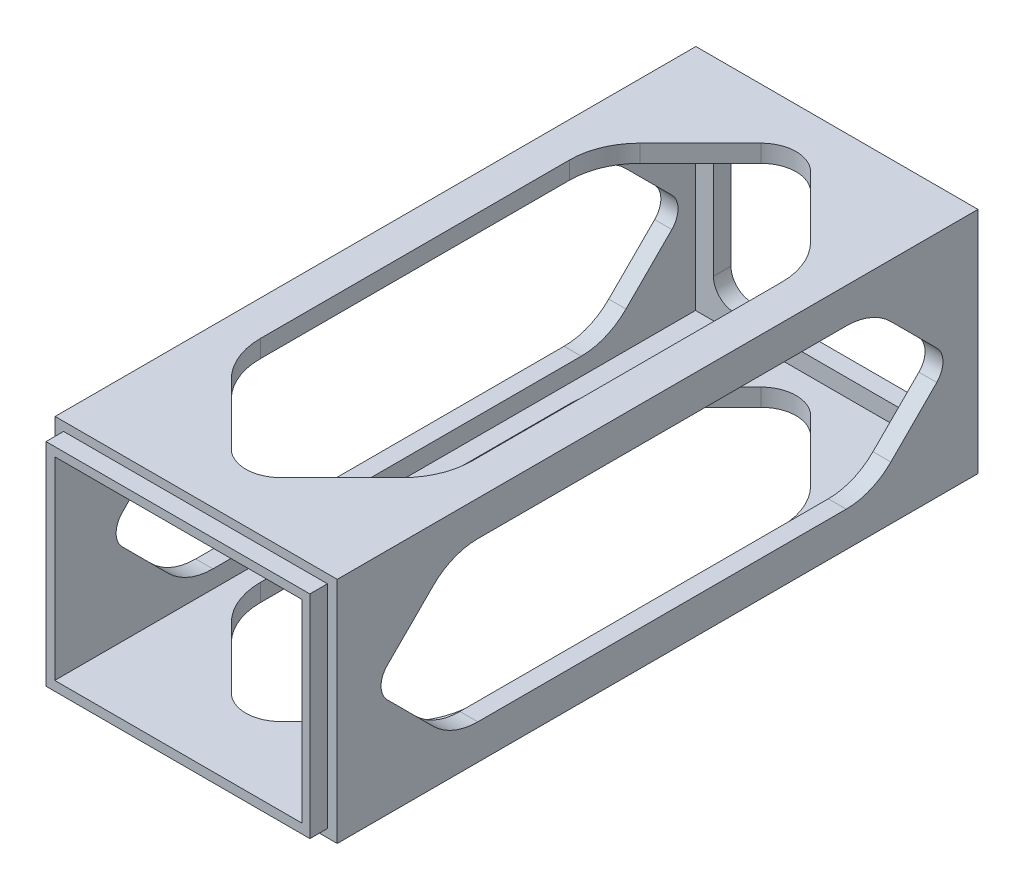
SolidWorks part; units mm, degrees
ref_plane "Front Plane" through (0, 0, 0) normal (0, 0, 1) x (1, 0, 0)
ref_plane "Top Plane" through (0, 0, 0) normal (0, 1, 0) x (1, 0, 0)
ref_plane "Right Plane" through (0, 0, 0) normal (1, 0, 0) x (0, 0, -1)
sketch "Sketch2" plane through (0, 0, 0) normal (0, 0, 1) x (1, 0, 0)
  line L0 (-29.7303, 22.4307) -> (18.0217, 22.4307)
  line L1 (-28.1428, 20.8432) -> (16.5612, 20.8432)
  line L2 (-28.1428, 20.8432) -> (-28.1428, -14.2088)
  line L3 (-28.1428, -14.2088) -> (16.5612, -14.2088)
  line L4 (16.5612, 20.8432) -> (16.5612, -14.2088)
  line L5 (-29.7303, -15.0684) -> (-29.7303, -15.9233)
  line L8 (-29.7303, 22.4307) -> (-29.7303, -15.0684)
  line L9 (-29.7303, -15.9233) -> (18.0217, -15.9233)
  line L10 (18.0217, 22.4307) -> (18.0217, -15.9233)
  dimension "D1" = 44.704
  dimension "D2" = 35.052
  dimension "D5" = 47.752
  dimension "D6" = 38.354
extrude "Boss-Extrude1" add sketch "Sketch2" along normal blind 119.126
sketch "Sketch4" plane through (0, 0, 0) normal (0, 0, -1) x (-1, 0, 0)
  line L0 (31.2543, 24.0182) -> (-19.7997, 24.0182)
  line L1 (-18.0217, 22.4307) -> (29.7303, 22.4307)
  line L2 (29.7303, -15.9233) -> (-18.0217, -15.9233)
  line L3 (31.2543, 24.0182) -> (31.2543, -17.3838)
  line L4 (29.7303, -15.9233) -> (29.7303, 22.4307)
  line L5 (-19.7997, -17.3838) -> (31.2543, -17.3838)
  line L6 (-18.0217, 22.4307) -> (-18.0217, -15.9233)
  line L7 (-19.7997, -17.3838) -> (-19.7997, 24.0182)
  dimension "D1" = 47.752
  dimension "D2" = 51.054
  dimension "D3" = 41.402
extrude "Boss-Extrude2" add sketch "Sketch4" against normal blind 115.951
sketch "Sketch5" plane through (0, 0, 0) normal (0, 0, -1) x (-1, 0, 0)
  line L1 (31.2543, 24.0182) -> (-19.7997, 24.0182)
  line L2 (31.2543, 24.0182) -> (31.2543, -17.3838)
  line L3 (31.2543, -17.3838) -> (-19.7997, -17.3838)
  line L4 (-19.7997, 24.0182) -> (-19.7997, -17.3838)
extrude "Boss-Extrude3" add sketch "Sketch5" against normal blind 3.175
sketch "Sketch6" plane through (0, 0, 3.175) normal (0, 0, 1) x (1, 0, 0)
  line L12 (-21.0943, 17.6682) -> (9.6397, 17.6682)
  line L13 (-24.9043, 13.8582) -> (-24.9043, -7.2238)
  line L14 (-21.0943, -11.0338) -> (9.6397, -11.0338)
  line L15 (13.4497, 13.8582) -> (13.4497, -7.2238)
  arc A0 (-24.9043, -7.2238) -> (-21.0943, -11.0338) centre (-21.0943, -7.2238) ccw
  arc A1 (9.6397, -11.0338) -> (13.4497, -7.2238) centre (9.6397, -7.2238) ccw
  arc A2 (13.4497, 13.8582) -> (9.6397, 17.6682) centre (9.6397, 13.8582) ccw
  arc A3 (-21.0943, 17.6682) -> (-24.9043, 13.8582) centre (-21.0943, 13.8582) ccw
  dimension "D1" = 3.81
extrude "Cut-Extrude1" cut sketch "Sketch6" against normal blind 6.35
sketch "Sketch7" plane through (19.7997, 0, 0) normal (-1, 0, 0) x (0, 0, 1)
  line L8 (23.848, -11.0338) -> (90.5155, -11.0338)
  line L16 (98.5978, -7.686) -> (106.9069, 0.6232)
  line L17 (98.5978, 14.3205) -> (106.9069, 6.0113)
  line L18 (7.4566, 6.0113) -> (15.7657, 14.3205)
  line L19 (7.4566, 0.6232) -> (15.7657, -7.686)
  line L20 (23.848, 17.6682) -> (90.5155, 17.6682)
  arc A0 (23.848, -11.0338) -> (15.7657, -7.686) centre (23.848, 0.3962) cw
  arc A1 (90.5155, -11.0338) -> (98.5978, -7.686) centre (90.5155, 0.3962) ccw
  arc A2 (90.5155, 17.6682) -> (98.5978, 14.3205) centre (90.5155, 6.2382) cw
  arc A3 (23.848, 17.6682) -> (15.7657, 14.3205) centre (23.848, 6.2382) ccw
  arc A4 (106.9069, 0.6232) -> (106.9069, 6.0113) centre (104.2128, 3.3172) ccw
  arc A5 (7.4566, 6.0113) -> (7.4566, 0.6232) centre (10.1507, 3.3172) ccw
  dimension "D1" = 11.43
  dimension "D2" = 3.81
extrude "Cut-Extrude2" cut sketch "Sketch7" along normal through all
sketch "Sketch8" plane through (0, 24.0182, 0) normal (0, 1, 0) x (1, 0, 0)
  line L1 (-21.1845, -20.2198) -> (-10.2174, -9.2526)
  line L5 (9.73, -20.2198) -> (-1.2371, -9.2526)
  line L12 (-24.9043, -29.2) -> (-24.9043, -85.1635)
  line L15 (-21.1845, -94.1437) -> (-10.2174, -105.1109)
  line L16 (9.73, -94.1437) -> (-1.2371, -105.1109)
  line L17 (13.4497, -85.1635) -> (13.4497, -29.2)
  arc A0 (-24.9043, -85.1635) -> (-21.1845, -94.1437) centre (-12.2043, -85.1635) ccw
  arc A1 (13.4497, -85.1635) -> (9.73, -94.1437) centre (0.7497, -85.1635) cw
  arc A2 (13.4497, -29.2) -> (9.73, -20.2198) centre (0.7497, -29.2) ccw
  arc A3 (-21.1845, -20.2198) -> (-24.9043, -29.2) centre (-12.2043, -29.2) ccw
  arc A4 (-10.2174, -105.1109) -> (-1.2371, -105.1109) centre (-5.7273, -100.6207) ccw
  arc A5 (-1.2371, -9.2526) -> (-10.2174, -9.2526) centre (-5.7273, -13.7428) ccw
  dimension "D2" = 6.35
  dimension "D1" = 12.7
extrude "Cut-Extrude3" cut sketch "Sketch8" against normal through all contours L5 A5 L1 A3 L12 A0 L15 A4 L16 A1 L17 A2
